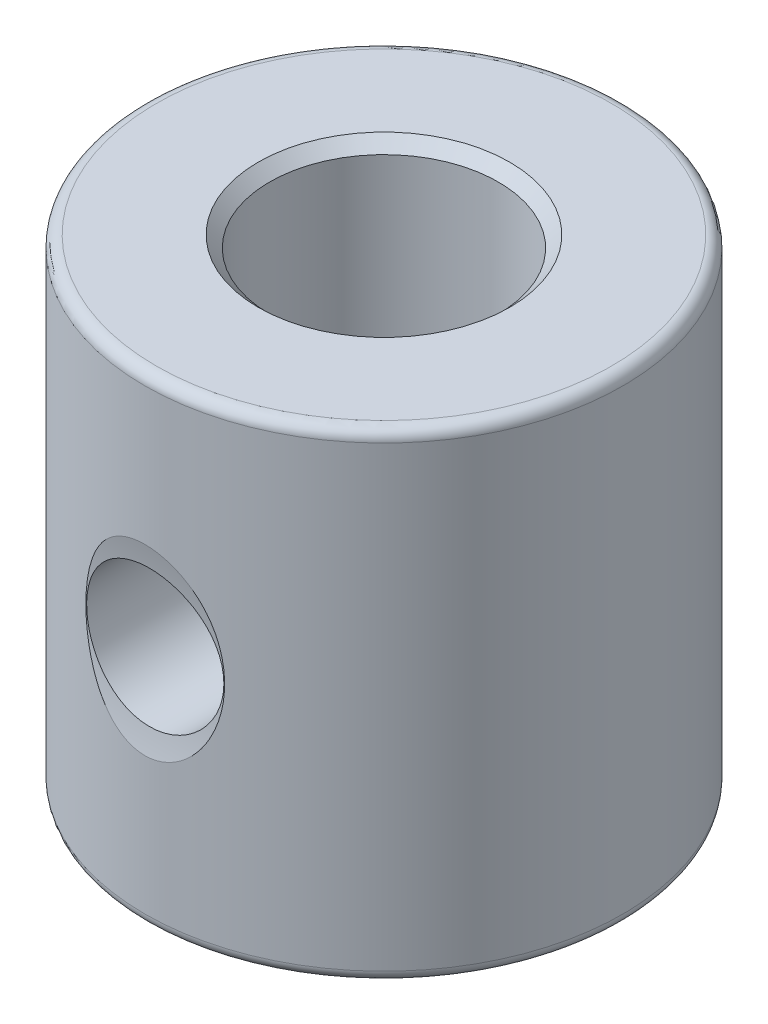
SolidWorks part; units mm, degrees
material "AISI 1045 Steel, cold drawn"
ref_plane "Front Plane" through (0, 0, 0) normal (0, 0, 1) x (1, 0, 0)
ref_plane "Top Plane" through (0, 0, 0) normal (0, 1, 0) x (1, 0, 0)
ref_plane "Right Plane" through (0, 0, 0) normal (1, 0, 0) x (0, 0, -1)
sketch "Sketch1" plane through (0, 0, 0) normal (0, 1, 0) x (1, 0, 0)
  circle A0 centre (0, 0) radius 5.225
  circle A1 centre (0, 0) radius 2.5
  dimension "D1" = 10.45
  dimension "D2" = 5
extrude "Boss-Extrude1" add sketch "Sketch1" along normal mid plane 10.5
sketch "Sketch2" plane through (0, 0, 0) normal (0, 0, 1) x (1, 0, 0)
  circle A0 centre (0, 0) radius 1.5
  dimension "D1" = 3
extrude "Cut-Extrude1" cut sketch "Sketch2" against normal mid plane 10.45
sketch "Sketch4" plane through (0, 0, 0) normal (1, 0, 0) x (0, 0, -1)
  circle A0 centre (-14, 0) radius 9
  dimension "D1" = 18
  dimension "D2" = 14
extrude "Cut-Extrude2" cut sketch "Sketch4" against normal through all both and the other way through all
fillet "Fillet1" radius 0.25 2 edges at (0, -5.25, 5.225) (0, 5.25, 5.225)
chamfer "Chamfer1" distance 0.25 angle 45 1 edges at (0, 5.25, 2.5)
